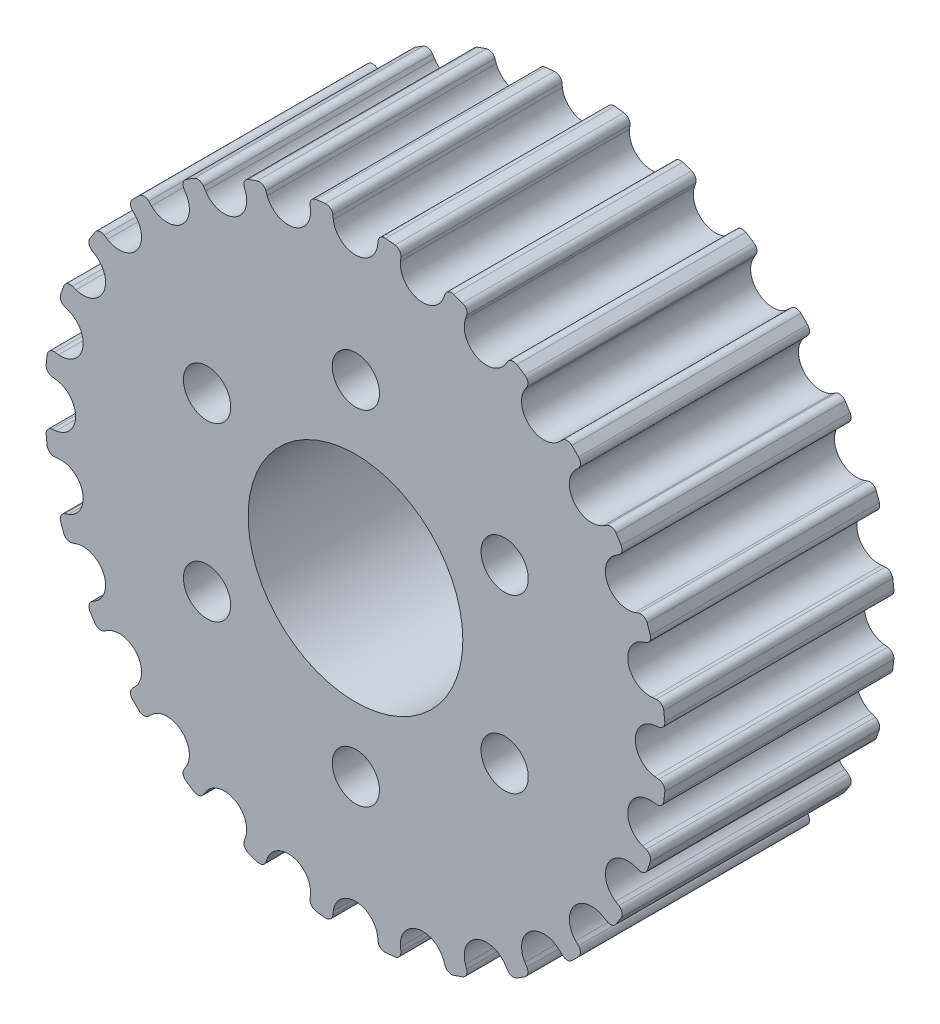
SolidWorks part; units mm, degrees
material "6061 合金"
ref_plane "前视基准面" through (0, 0, 0) normal (0, 0, 1) x (1, 0, 0)
ref_plane "上视基准面" through (0, 0, 0) normal (0, 1, 0) x (1, 0, 0)
ref_plane "右视基准面" through (0, 0, 0) normal (1, 0, 0) x (0, 0, -1)
sketch "草图1" plane through (0, 0, 0) normal (0, 0, 1) x (1, 0, 0)
  line L36 (1.554, 21.1844) -> (1.521, 20.9158)
  line L37 (-1.5757, 20.9158) -> (-1.6087, 21.1844)
  line L38 (-3.2001, 21.0051) -> (-3.1724, 20.7359)
  line L39 (-6.1915, 20.0468) -> (-6.2835, 20.3013)
  line L40 (-7.7951, 19.7724) -> (-7.7082, 19.5161)
  line L41 (-10.4983, 18.1724) -> (-10.6446, 18.4002)
  line L42 (-12.0006, 17.5481) -> (-11.8588, 17.3175)
  line L43 (-14.28, 15.3868) -> (-14.4733, 15.5762)
  line L44 (-15.6057, 14.4438) -> (-15.4162, 14.2505)
  line L45 (-17.347, 11.8294) -> (-17.5776, 11.9711)
  line L46 (-18.4296, 10.6151) -> (-18.2019, 10.4689)
  line L47 (-19.5455, 7.6788) -> (-19.8018, 7.7656)
  line L48 (-20.3308, 6.254) -> (-20.0762, 6.1621)
  line L49 (-20.7653, 3.143) -> (-21.0345, 3.1706)
  line L50 (-21.2138, 1.5792) -> (-20.9452, 1.5463)
  line L51 (-20.9452, -1.5505) -> (-21.2138, -1.5835)
  line L52 (-21.0345, -3.1748) -> (-20.7653, -3.1472)
  line L53 (-20.0762, -6.1663) -> (-20.3308, -6.2583)
  line L54 (-19.8018, -7.7698) -> (-19.5455, -7.683)
  line L55 (-18.2019, -10.4731) -> (-18.4296, -10.6194)
  line L56 (-17.5776, -11.9753) -> (-17.347, -11.8336)
  line L57 (-15.4162, -14.2548) -> (-15.6057, -14.448)
  line L58 (-14.4733, -15.5804) -> (-14.28, -15.391)
  line L59 (-11.8588, -17.3218) -> (-12.0006, -17.5524)
  line L60 (-10.6446, -18.4044) -> (-10.4983, -18.1767)
  line L61 (-7.7082, -19.5203) -> (-7.7951, -19.7766)
  line L62 (-6.2835, -20.3056) -> (-6.1915, -20.051)
  line L63 (-3.1724, -20.7401) -> (-3.2001, -21.0093)
  line L64 (-1.6087, -21.1886) -> (-1.5757, -20.92)
  line L65 (1.521, -20.92) -> (1.554, -21.1886)
  line L66 (3.1454, -21.0093) -> (3.1178, -20.7401)
  line L67 (6.1369, -20.051) -> (6.2288, -20.3056)
  line L68 (7.7404, -19.7766) -> (7.6536, -19.5203)
  line L69 (10.4436, -18.1767) -> (10.5899, -18.4044)
  line L70 (11.9459, -17.5524) -> (11.8042, -17.3218)
  line L71 (14.2253, -15.391) -> (14.4186, -15.5804)
  line L72 (15.551, -14.448) -> (15.3615, -14.2548)
  line L73 (17.2923, -11.8336) -> (17.5229, -11.9753)
  line L74 (18.375, -10.6194) -> (18.1472, -10.4731)
  line L75 (19.4909, -7.683) -> (19.7472, -7.7698)
  line L76 (20.2761, -6.2583) -> (20.0216, -6.1663)
  line L77 (20.7107, -3.1472) -> (20.9799, -3.1748)
  line L78 (21.1592, -1.5835) -> (20.8906, -1.5505)
  line L79 (20.8906, 1.5463) -> (21.1592, 1.5792)
  line L80 (20.9799, 3.1706) -> (20.7107, 3.143)
  line L81 (20.0216, 6.1621) -> (20.2761, 6.254)
  line L82 (19.7472, 7.7656) -> (19.4909, 7.6788)
  line L83 (18.1472, 10.4689) -> (18.375, 10.6151)
  line L84 (17.5229, 11.9711) -> (17.2923, 11.8294)
  line L85 (15.3615, 14.2505) -> (15.551, 14.4438)
  line L86 (14.4186, 15.5762) -> (14.2253, 15.3868)
  line L87 (11.8042, 17.3175) -> (11.9459, 17.5481)
  line L88 (10.5899, 18.4002) -> (10.4436, 18.1724)
  line L89 (7.6536, 19.5161) -> (7.7404, 19.7724)
  line L90 (6.2288, 20.3013) -> (6.1369, 20.0468)
  line L91 (3.1178, 20.7359) -> (3.1454, 21.0051)
  circle A72 centre (0, 0) radius 12 construction
  arc A73 (3.1454, 21.0051) -> (2.7289, 21.5302) centre (2.6679, 21.0541) ccw
  arc A74 (2.7289, 21.5302) -> (2.077, 21.6037) centre (-0.0273, -0.0021) ccw
  arc A75 (2.077, 21.6037) -> (1.554, 21.1844) centre (2.0305, 21.1259) ccw
  arc A76 (-1.5757, 20.9158) -> (1.521, 20.9158) centre (-0.0273, 21.1059) ccw
  arc A77 (-1.6087, 21.1844) -> (-2.1316, 21.6037) centre (-2.0851, 21.1259) ccw
  arc A78 (-2.1316, 21.6037) -> (-2.7835, 21.5302) centre (-0.0273, -0.0021) ccw
  arc A79 (-2.7835, 21.5302) -> (-3.2001, 21.0051) centre (-2.7226, 21.0541) ccw
  arc A80 (-6.1915, 20.0468) -> (-3.1724, 20.7359) centre (-4.7243, 20.5767) ccw
  arc A81 (-6.2835, 20.3013) -> (-6.8866, 20.5937) centre (-6.7349, 20.1383) ccw
  arc A82 (-6.8866, 20.5937) -> (-7.5058, 20.377) centre (-0.0273, -0.0021) ccw
  arc A83 (-7.5058, 20.377) -> (-7.7951, 19.7724) centre (-7.3404, 19.9264) ccw
  arc A84 (-10.4983, 18.1724) -> (-7.7082, 19.5161) centre (-9.1857, 19.0155) ccw
  arc A85 (-10.6446, 18.4002) -> (-11.2976, 18.551) centre (-11.0484, 18.1407) ccw
  arc A86 (-11.2976, 18.551) -> (-11.8531, 18.202) centre (-0.0273, -0.0021) ccw
  arc A87 (-11.8531, 18.202) -> (-12.0006, 17.5481) centre (-11.5916, 17.7994) ccw
  arc A88 (-14.28, 15.3868) -> (-11.8588, 17.3175) centre (-13.1879, 16.5008) ccw
  arc A89 (-14.4733, 15.5762) -> (-15.1435, 15.5779) centre (-14.8093, 15.2334) ccw
  arc A90 (-15.1435, 15.5779) -> (-15.6074, 15.1141) centre (-0.0273, -0.0021) ccw
  arc A91 (-15.6074, 15.1141) -> (-15.6057, 14.4438) centre (-15.2629, 14.7798) ccw
  arc A92 (-17.347, 11.8294) -> (-15.4162, 14.2505) centre (-16.5302, 13.1585) ccw
  arc A93 (-17.5776, 11.9711) -> (-18.2314, 11.8236) centre (-17.8289, 11.5622) ccw
  arc A94 (-18.2314, 11.8236) -> (-18.5804, 11.2682) centre (-0.0273, -0.0021) ccw
  arc A95 (-18.5804, 11.2682) -> (-18.4296, 10.6151) centre (-18.1702, 11.019) ccw
  arc A96 (-19.5455, 7.6788) -> (-18.2019, 10.4689) centre (-19.045, 9.1563) ccw
  arc A97 (-19.8018, 7.7656) -> (-20.4065, 7.4764) centre (-19.9559, 7.311) ccw
  arc A98 (-20.4065, 7.4764) -> (-20.6231, 6.8572) centre (-0.0273, -0.0021) ccw
  arc A99 (-20.6231, 6.8572) -> (-20.3308, 6.254) centre (-20.1677, 6.7055) ccw
  arc A100 (-20.7653, 3.143) -> (-20.0762, 6.1621) centre (-20.6061, 4.6949) ccw
  arc A101 (-21.0345, 3.1706) -> (-21.5596, 2.7541) centre (-21.0835, 2.6931) ccw
  arc A102 (-21.5596, 2.7541) -> (-21.6331, 2.1022) centre (-0.0273, -0.0021) ccw
  arc A103 (-21.6331, 2.1022) -> (-21.2138, 1.5792) centre (-21.1554, 2.0557) ccw
  arc A104 (-20.9452, -1.5505) -> (-20.9452, 1.5463) centre (-21.1353, -0.0021) ccw
  arc A105 (-21.2138, -1.5835) -> (-21.6331, -2.1064) centre (-21.1554, -2.0599) ccw
  arc A106 (-21.6331, -2.1064) -> (-21.5596, -2.7583) centre (-0.0273, -0.0021) ccw
  arc A107 (-21.5596, -2.7583) -> (-21.0345, -3.1748) centre (-21.0835, -2.6974) ccw
  arc A108 (-20.0762, -6.1663) -> (-20.7653, -3.1472) centre (-20.6061, -4.6991) ccw
  arc A109 (-20.3308, -6.2583) -> (-20.6231, -6.8614) centre (-20.1677, -6.7097) ccw
  arc A110 (-20.6231, -6.8614) -> (-20.4065, -7.4806) centre (-0.0273, -0.0021) ccw
  arc A111 (-20.4065, -7.4806) -> (-19.8018, -7.7698) centre (-19.9559, -7.3152) ccw
  arc A112 (-18.2019, -10.4731) -> (-19.5455, -7.683) centre (-19.045, -9.1605) ccw
  arc A113 (-18.4296, -10.6194) -> (-18.5804, -11.2724) centre (-18.1702, -11.0232) ccw
  arc A114 (-18.5804, -11.2724) -> (-18.2314, -11.8279) centre (-0.0273, -0.0021) ccw
  arc A115 (-18.2314, -11.8279) -> (-17.5776, -11.9753) centre (-17.8289, -11.5664) ccw
  arc A116 (-15.4162, -14.2548) -> (-17.347, -11.8336) centre (-16.5302, -13.1627) ccw
  arc A117 (-15.6057, -14.448) -> (-15.6074, -15.1183) centre (-15.2629, -14.7841) ccw
  arc A118 (-15.6074, -15.1183) -> (-15.1435, -15.5822) centre (-0.0273, -0.0021) ccw
  arc A119 (-15.1435, -15.5822) -> (-14.4733, -15.5804) centre (-14.8093, -15.2377) ccw
  arc A120 (-11.8588, -17.3218) -> (-14.28, -15.391) centre (-13.1879, -16.505) ccw
  arc A121 (-12.0006, -17.5524) -> (-11.8531, -18.2062) centre (-11.5916, -17.8037) ccw
  arc A122 (-11.8531, -18.2062) -> (-11.2976, -18.5552) centre (-0.0273, -0.0021) ccw
  arc A123 (-11.2976, -18.5552) -> (-10.6446, -18.4044) centre (-11.0484, -18.145) ccw
  arc A124 (-7.7082, -19.5203) -> (-10.4983, -18.1767) centre (-9.1857, -19.0198) ccw
  arc A125 (-7.7951, -19.7766) -> (-7.5058, -20.3813) centre (-7.3404, -19.9306) ccw
  arc A126 (-7.5058, -20.3813) -> (-6.8866, -20.5979) centre (-0.0273, -0.0021) ccw
  arc A127 (-6.8866, -20.5979) -> (-6.2835, -20.3056) centre (-6.7349, -20.1425) ccw
  arc A128 (-3.1724, -20.7401) -> (-6.1915, -20.051) centre (-4.7243, -20.5809) ccw
  arc A129 (-3.2001, -21.0093) -> (-2.7835, -21.5344) centre (-2.7226, -21.0583) ccw
  arc A130 (-2.7835, -21.5344) -> (-2.1316, -21.6079) centre (-0.0273, -0.0021) ccw
  arc A131 (-2.1316, -21.6079) -> (-1.6087, -21.1886) centre (-2.0851, -21.1301) ccw
  arc A132 (1.521, -20.92) -> (-1.5757, -20.92) centre (-0.0273, -21.1101) ccw
  arc A133 (1.554, -21.1886) -> (2.077, -21.6079) centre (2.0305, -21.1301) ccw
  arc A134 (2.077, -21.6079) -> (2.7289, -21.5344) centre (-0.0273, -0.0021) ccw
  arc A135 (2.7289, -21.5344) -> (3.1454, -21.0093) centre (2.6679, -21.0583) ccw
  arc A136 (6.1369, -20.051) -> (3.1178, -20.7401) centre (4.6696, -20.5809) ccw
  arc A137 (6.2288, -20.3056) -> (6.832, -20.5979) centre (6.6803, -20.1425) ccw
  arc A138 (6.832, -20.5979) -> (7.4512, -20.3813) centre (-0.0273, -0.0021) ccw
  arc A139 (7.4512, -20.3813) -> (7.7404, -19.7766) centre (7.2858, -19.9306) ccw
  arc A140 (10.4436, -18.1767) -> (7.6536, -19.5203) centre (9.1311, -19.0198) ccw
  arc A141 (10.5899, -18.4044) -> (11.243, -18.5552) centre (10.9938, -18.145) ccw
  arc A142 (11.243, -18.5552) -> (11.7984, -18.2062) centre (-0.0273, -0.0021) ccw
  arc A143 (11.7984, -18.2062) -> (11.9459, -17.5524) centre (11.5369, -17.8037) ccw
  arc A144 (14.2253, -15.391) -> (11.8042, -17.3218) centre (13.1333, -16.505) ccw
  arc A145 (14.4186, -15.5804) -> (15.0889, -15.5822) centre (14.7546, -15.2377) ccw
  arc A146 (15.0889, -15.5822) -> (15.5527, -15.1183) centre (-0.0273, -0.0021) ccw
  arc A147 (15.5527, -15.1183) -> (15.551, -14.448) centre (15.2082, -14.7841) ccw
  arc A148 (17.2923, -11.8336) -> (15.3615, -14.2548) centre (16.4756, -13.1627) ccw
  arc A149 (17.5229, -11.9753) -> (18.1768, -11.8279) centre (17.7742, -11.5664) ccw
  arc A150 (18.1768, -11.8279) -> (18.5258, -11.2724) centre (-0.0273, -0.0021) ccw
  arc A151 (18.5258, -11.2724) -> (18.375, -10.6194) centre (18.1155, -11.0232) ccw
  arc A152 (19.4909, -7.683) -> (18.1472, -10.4731) centre (18.9903, -9.1605) ccw
  arc A153 (19.7472, -7.7698) -> (20.3518, -7.4806) centre (19.9012, -7.3152) ccw
  arc A154 (20.3518, -7.4806) -> (20.5685, -6.8614) centre (-0.0273, -0.0021) ccw
  arc A155 (20.5685, -6.8614) -> (20.2761, -6.2583) centre (20.1131, -6.7097) ccw
  arc A156 (20.7107, -3.1472) -> (20.0216, -6.1663) centre (20.5515, -4.6991) ccw
  arc A157 (20.9799, -3.1748) -> (21.505, -2.7583) centre (21.0289, -2.6974) ccw
  arc A158 (21.505, -2.7583) -> (21.5784, -2.1064) centre (-0.0273, -0.0021) ccw
  arc A159 (21.5784, -2.1064) -> (21.1592, -1.5835) centre (21.1007, -2.0599) ccw
  arc A160 (20.8906, 1.5463) -> (20.8906, -1.5505) centre (21.0807, -0.0021) ccw
  arc A161 (21.1592, 1.5792) -> (21.5784, 2.1022) centre (21.1007, 2.0557) ccw
  arc A162 (21.5784, 2.1022) -> (21.505, 2.7541) centre (-0.0273, -0.0021) ccw
  arc A163 (21.505, 2.7541) -> (20.9799, 3.1706) centre (21.0289, 2.6931) ccw
  arc A164 (20.0216, 6.1621) -> (20.7107, 3.143) centre (20.5515, 4.6949) ccw
  arc A165 (20.2761, 6.254) -> (20.5685, 6.8572) centre (20.1131, 6.7055) ccw
  arc A166 (20.5685, 6.8572) -> (20.3518, 7.4764) centre (-0.0273, -0.0021) ccw
  arc A167 (20.3518, 7.4764) -> (19.7472, 7.7656) centre (19.9012, 7.311) ccw
  arc A168 (18.1472, 10.4689) -> (19.4909, 7.6788) centre (18.9903, 9.1563) ccw
  arc A169 (18.375, 10.6151) -> (18.5258, 11.2682) centre (18.1155, 11.019) ccw
  arc A170 (18.5258, 11.2682) -> (18.1768, 11.8236) centre (-0.0273, -0.0021) ccw
  arc A171 (18.1768, 11.8236) -> (17.5229, 11.9711) centre (17.7742, 11.5622) ccw
  arc A172 (15.3615, 14.2505) -> (17.2923, 11.8294) centre (16.4756, 13.1585) ccw
  arc A173 (15.551, 14.4438) -> (15.5527, 15.1141) centre (15.2082, 14.7798) ccw
  arc A174 (15.5527, 15.1141) -> (15.0889, 15.5779) centre (-0.0273, -0.0021) ccw
  arc A175 (15.0889, 15.5779) -> (14.4186, 15.5762) centre (14.7546, 15.2334) ccw
  arc A176 (11.8042, 17.3175) -> (14.2253, 15.3868) centre (13.1333, 16.5008) ccw
  arc A177 (11.9459, 17.5481) -> (11.7984, 18.202) centre (11.5369, 17.7994) ccw
  arc A178 (11.7984, 18.202) -> (11.243, 18.551) centre (-0.0273, -0.0021) ccw
  arc A179 (11.243, 18.551) -> (10.5899, 18.4002) centre (10.9938, 18.1407) ccw
  arc A180 (7.6536, 19.5161) -> (10.4436, 18.1724) centre (9.1311, 19.0155) ccw
  arc A181 (7.7404, 19.7724) -> (7.4512, 20.377) centre (7.2858, 19.9264) ccw
  arc A182 (7.4512, 20.377) -> (6.832, 20.5937) centre (-0.0273, -0.0021) ccw
  arc A183 (6.832, 20.5937) -> (6.2288, 20.3013) centre (6.6803, 20.1383) ccw
  arc A184 (3.1178, 20.7359) -> (6.1369, 20.0468) centre (4.6696, 20.5767) ccw
  circle A185 centre (-0.0273, -0.0021) radius 7.5
  dimension "D1" = 15
  dimension "D2" = 24
extrude "凸台-拉伸1" add sketch "草图1" along normal blind 16
sketch "草图7" plane through (0, 0, 0) normal (0, 0, -1) x (-1, 0, 0)
  circle A0 centre (0, 0) radius 12 construction
  circle A8 centre (0, 12) radius 1.65
  circle A9 centre (10.3923, 6) radius 1.65
  circle A10 centre (10.3923, -6) radius 1.65
  circle A11 centre (0, -12) radius 1.65
  circle A12 centre (-10.3923, -6) radius 1.65
  circle A13 centre (-10.3923, 6) radius 1.65
  point P3 (0, 12)
  point P6 (10.3923, 6)
  point P7 (10.3923, -6)
  point P8 (0, -12)
  point P9 (-10.3923, -6)
  point P10 (-10.3923, 6)
  point P11 (0, 0)
  point P24 (0, 0)
  point P26 (0, 0)
  dimension "D1" = 24
  dimension "D3" = 6
  dimension "D4" = 3.3
  dimension "D2" = 6
ref_plane "基准面1" through (0, 0, -10) normal (0, 0, -1) x (-1, 0, 0)
sketch "草图8" plane through (0, 0, -10) normal (0, 0, -1) x (-1, 0, 0)
  circle A0 centre (0, 0) radius 12 construction
ref_plane "基准面2" through (0, 0, 0) normal (0, 0, -1) x (-1, 0, 0)
sketch "草图9" plane through (0, 0, 0) normal (0, 0, -1) x (-1, 0, 0)
  circle A0 centre (0, 12) radius 1.65
  circle A1 centre (0, 0) radius 12 construction
  circle A2 centre (10.3923, 6) radius 1.65
  circle A3 centre (10.3923, -6) radius 1.65
  circle A4 centre (0, -12) radius 1.65
  circle A5 centre (-10.3923, -6) radius 1.65
  circle A6 centre (-10.3923, 6) radius 1.65
  point P16 (0, 0)
  dimension "D1" = 6
extrude "切除-拉伸2" cut sketch "草图9" against normal blind 16
extrude "切除-拉伸1" cut sketch "草图7" against normal blind 41
